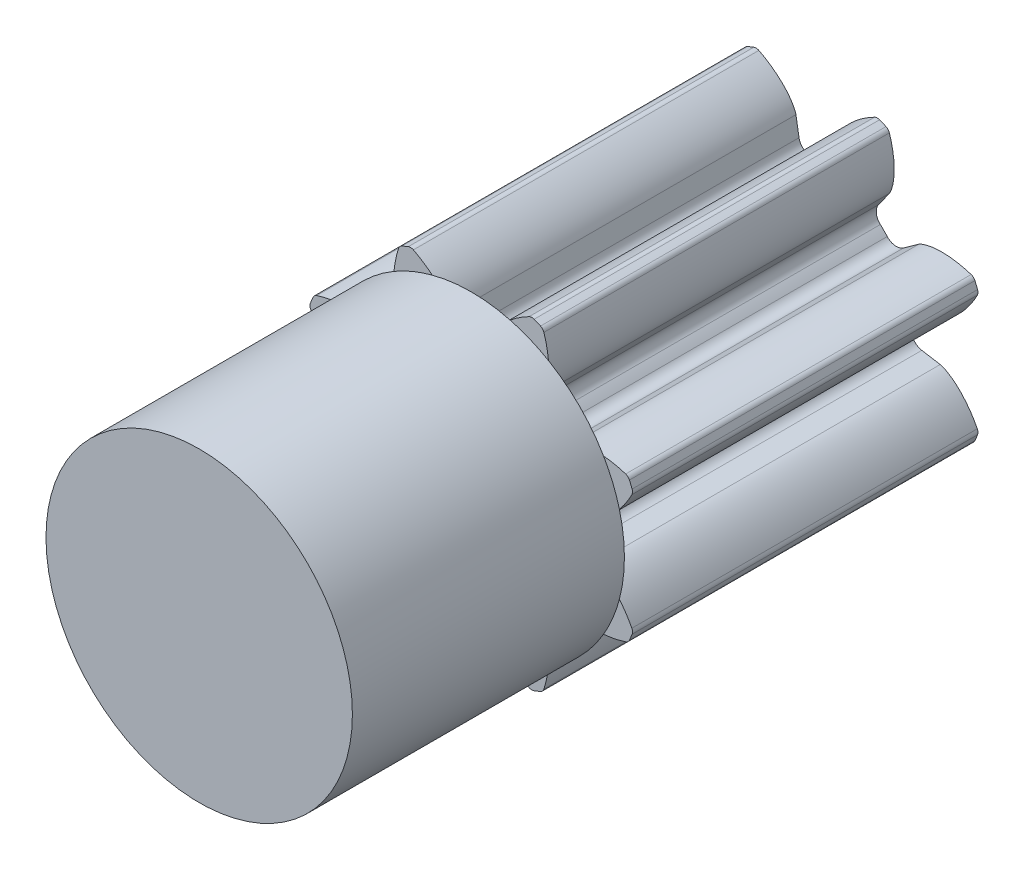
SolidWorks part; units mm, degrees
material "Alloy Steel"
ref_plane "Front" through (0, 0, 0) normal (0, 0, 1) x (1, 0, 0)
ref_plane "Top" through (0, 0, 0) normal (0, 1, 0) x (1, 0, 0)
ref_plane "Right" through (0, 0, 0) normal (1, 0, 0) x (0, 0, -1)
sketch "Sketch1" plane through (0, 0, 0) normal (0, 0, 1) x (1, 0, 0)
  circle A0 centre (0, 0) radius 6.35
extrude "Boss-Extrude1" add sketch "Sketch1" along normal blind 12.7
sketch "Sketch3" plane through (0, 0, 0) normal (0, 0, 1) x (1, 0, 0)
  line L0 (0, 0) -> (43.7181, 0) construction
  line L2 (0, 0) -> (-0.5784, 3.4443) construction
  line L3 (0, 0) -> (0.5784, 3.4443) construction
  line L4 (0.5784, 3.4443) -> (0.7625, 4.5405) construction
  line L5 (0, 0) -> (0, 61.276) construction
  line L6 (-0.5784, 3.4443) -> (-0.7625, 4.5405) construction
  circle A0 centre (0, 0) radius 6.35 construction
  circle A1 centre (0, 0) radius 5.08 construction
  circle A2 centre (0, 0) radius 4.604 construction
  arc A3 (0.5784, 3.4443) -> (-0.5784, 3.4443) centre (0, 0) ccw construction
  arc A5 (2.2164, 5.9506) -> (-2.2164, 5.9506) centre (0, 0) ccw
  spline S0 degree 4 poles (-0.7625, 4.5405) (-0.763, 4.5435) (-0.7648, 4.5519) (-0.7689, 4.5677) (-0.7767, 4.5932) (-0.7881, 4.6252) (-0.8045, 4.666) (-0.826, 4.7133) (-0.852, 4.7644) (-0.8825, 4.8189) (-0.9151, 4.8722) (-0.9496, 4.9244) (-0.9856, 4.9755) (-1.0311, 5.0363) (-1.0885, 5.1074) (-1.1594, 5.1881) (-1.2442, 5.2764) (-1.3353, 5.3629) (-1.4285, 5.4451) (-1.5269, 5.5244) (-1.6249, 5.5987) (-1.7306, 5.6719) (-1.8302, 5.7375) (-1.9458, 5.8065) (-2.0404, 5.8609) (-2.1692, 5.9277) (-2.2466, 5.9657) (-2.3384, 6.0084) (-2.3799, 6.0264) (-2.4054, 6.0376) knots 0 0 0 0 0 0.005377 0.015084 0.028532 0.04661 0.064855 0.092111 0.119476 0.146842 0.174209 0.201575 0.228941 0.256307 0.307035 0.361767 0.4165 0.471232 0.525964 0.580697 0.635429 0.690161 0.744894 0.799626 0.854358 0.909091 0.954545 1 1 1 1 1 construction
  spline S1 degree 4 poles (-0.7625, 4.5405) (-0.763, 4.5435) (-0.7648, 4.5519) (-0.7689, 4.5677) (-0.7767, 4.5932) (-0.7881, 4.6252) (-0.8045, 4.666) (-0.826, 4.7133) (-0.852, 4.7644) (-0.8825, 4.8189) (-0.9151, 4.8722) (-0.9496, 4.9244) (-0.9856, 4.9755) (-1.0311, 5.0363) (-1.0885, 5.1074) (-1.1594, 5.1881) (-1.2442, 5.2764) (-1.3353, 5.3629) (-1.4285, 5.4451) (-1.5269, 5.5244) (-1.6249, 5.5987) (-1.7306, 5.6719) (-1.8302, 5.7375) (-1.9458, 5.8065) (-2.0404, 5.8609) (-2.1413, 5.9133) (-2.1909, 5.9381) (-2.2164, 5.9506) knots 0 0 0 0 0 0.005377 0.015084 0.028532 0.04661 0.064855 0.092111 0.119476 0.146842 0.174209 0.201575 0.228941 0.256307 0.307035 0.361767 0.4165 0.471232 0.525964 0.580697 0.635429 0.690161 0.744894 0.799626 0.854358 0.909091 0.909091 0.909091 0.909091 0.909091
  spline S2 degree 4 poles (0.7625, 4.5405) (0.763, 4.5435) (0.7648, 4.5519) (0.7689, 4.5677) (0.7767, 4.5932) (0.7881, 4.6252) (0.8045, 4.666) (0.826, 4.7133) (0.852, 4.7644) (0.8825, 4.8189) (0.9151, 4.8722) (0.9496, 4.9244) (0.9856, 4.9755) (1.0311, 5.0363) (1.0885, 5.1074) (1.1594, 5.1881) (1.2442, 5.2764) (1.3353, 5.3629) (1.4285, 5.4451) (1.5269, 5.5244) (1.6249, 5.5987) (1.7306, 5.6719) (1.8302, 5.7375) (1.9458, 5.8065) (2.0404, 5.8609) (2.1692, 5.9277) (2.2466, 5.9657) (2.3384, 6.0084) (2.3799, 6.0264) (2.4054, 6.0376) knots 0 0 0 0 0 0.005377 0.015084 0.028532 0.04661 0.064855 0.092111 0.119476 0.146842 0.174209 0.201575 0.228941 0.256307 0.307035 0.361767 0.4165 0.471232 0.525964 0.580697 0.635429 0.690161 0.744894 0.799626 0.854358 0.909091 0.954545 1 1 1 1 1 construction
  spline S3 degree 4 poles (0.7625, 4.5405) (0.763, 4.5435) (0.7648, 4.5519) (0.7689, 4.5677) (0.7767, 4.5932) (0.7881, 4.6252) (0.8045, 4.666) (0.826, 4.7133) (0.852, 4.7644) (0.8825, 4.8189) (0.9151, 4.8722) (0.9496, 4.9244) (0.9856, 4.9755) (1.0311, 5.0363) (1.0885, 5.1074) (1.1594, 5.1881) (1.2442, 5.2764) (1.3353, 5.3629) (1.4285, 5.4451) (1.5269, 5.5244) (1.6249, 5.5987) (1.7306, 5.6719) (1.8302, 5.7375) (1.9458, 5.8065) (2.0404, 5.8609) (2.1413, 5.9133) (2.1909, 5.9381) (2.2164, 5.9506) knots 0 0 0 0 0 0.005377 0.015084 0.028532 0.04661 0.064855 0.092111 0.119476 0.146842 0.174209 0.201575 0.228941 0.256307 0.307035 0.361767 0.4165 0.471232 0.525964 0.580697 0.635429 0.690161 0.744894 0.799626 0.854358 0.909091 0.909091 0.909091 0.909091 0.909091
  point P0 (0, 3.4925)
sketch "DCLTBC" plane through (0, 0, 0) normal (0, 0, 1) x (1, 0, 0)
  line L0 (0, 0) -> (41.04, 0) construction
  line L1 (-0.5784, 3.4443) -> (-0.7625, 4.5405) construction
  line L2 (0.5784, 3.4443) -> (0.7625, 4.5405) construction
  line L3 (-0.5784, 3.4443) -> (-0.7625, 4.5405)
  line L4 (0.5784, 3.4443) -> (0.7625, 4.5405)
  line L5 (0, 0) -> (0, 104.9356) construction
  circle A0 centre (0, 0) radius 6.35
  circle A1 centre (0, 0) radius 5.08 construction
  circle A2 centre (0, 0) radius 4.604 construction
  arc A3 (0.5784, 3.4443) -> (-0.5784, 3.4443) centre (0, 0) ccw construction
  arc A4 (0.5784, 3.4443) -> (-0.5784, 3.4443) centre (0, 0) ccw
  spline S0 degree 4 poles (-985.3765, -170.0538) (-13.2322, 1.3996) (-0.8474, 3.8586) (-0.6755, 4.2604) (-0.7767, 4.5932) (-0.7881, 4.6252) (-0.8045, 4.666) (-0.826, 4.7133) (-0.852, 4.7644) (-0.8825, 4.8189) (-0.9151, 4.8722) (-0.9496, 4.9244) (-0.9856, 4.9755) (-1.0311, 5.0363) (-1.0885, 5.1074) (-1.1594, 5.1881) (-1.2442, 5.2764) (-1.3353, 5.3629) (-1.4285, 5.4451) (-1.5269, 5.5244) (-1.6249, 5.5987) (-1.7306, 5.6719) (-1.8302, 5.7375) (-1.9458, 5.8065) (-2.4469, 6.0948) (-4.2835, 6.892) (20.1681, -5.2427) (-900.8438, 444.5764) knots -0.5622 -0.5622 -0.5622 -0.5622 -0.5622 0.005377 0.015084 0.028532 0.04661 0.064855 0.092111 0.119476 0.146842 0.174209 0.201575 0.228941 0.256307 0.307035 0.361767 0.4165 0.471232 0.525964 0.580697 0.635429 0.690161 0.744894 0.799626 0.854358 1.850205 1.850205 1.850205 1.850205 1.850205 only from (-0.7625, 4.5405) to (-2.2164, 5.9506) construction
  spline S1 degree 4 poles (985.3765, -170.0538) (13.2322, 1.3996) (0.8474, 3.8586) (0.6755, 4.2604) (0.7767, 4.5932) (0.7881, 4.6252) (0.8045, 4.666) (0.826, 4.7133) (0.852, 4.7644) (0.8825, 4.8189) (0.9151, 4.8722) (0.9496, 4.9244) (0.9856, 4.9755) (1.0311, 5.0363) (1.0885, 5.1074) (1.1594, 5.1881) (1.2442, 5.2764) (1.3353, 5.3629) (1.4285, 5.4451) (1.5269, 5.5244) (1.6249, 5.5987) (1.7306, 5.6719) (1.8302, 5.7375) (1.9458, 5.8065) (2.4469, 6.0948) (4.2835, 6.892) (-20.1681, -5.2427) (900.8438, 444.5764) knots -0.5622 -0.5622 -0.5622 -0.5622 -0.5622 0.005377 0.015084 0.028532 0.04661 0.064855 0.092111 0.119476 0.146842 0.174209 0.201575 0.228941 0.256307 0.307035 0.361767 0.4165 0.471232 0.525964 0.580697 0.635429 0.690161 0.744894 0.799626 0.854358 1.850205 1.850205 1.850205 1.850205 1.850205 only from (0.7625, 4.5405) to (2.2164, 5.9506) construction
  spline S2 degree 4 poles (-0.7625, 4.5405) (-0.763, 4.5435) (-0.7648, 4.5519) (-0.7689, 4.5677) (-0.7767, 4.5932) (-0.7881, 4.6252) (-0.8045, 4.666) (-0.826, 4.7133) (-0.852, 4.7644) (-0.8825, 4.8189) (-0.9151, 4.8722) (-0.9496, 4.9244) (-0.9856, 4.9755) (-1.0311, 5.0363) (-1.0885, 5.1074) (-1.1594, 5.1881) (-1.2442, 5.2764) (-1.3353, 5.3629) (-1.4285, 5.4451) (-1.5269, 5.5244) (-1.6249, 5.5987) (-1.7306, 5.6719) (-1.8302, 5.7375) (-1.9458, 5.8065) (-2.0404, 5.8609) (-2.1413, 5.9133) (-2.1909, 5.9381) (-2.2164, 5.9506) knots 0 0 0 0 0 0.005377 0.015084 0.028532 0.04661 0.064855 0.092111 0.119476 0.146842 0.174209 0.201575 0.228941 0.256307 0.307035 0.361767 0.4165 0.471232 0.525964 0.580697 0.635429 0.690161 0.744894 0.799626 0.854358 0.909091 0.909091 0.909091 0.909091 0.909091
  spline S3 degree 4 poles (0.7625, 4.5405) (0.763, 4.5435) (0.7648, 4.5519) (0.7689, 4.5677) (0.7767, 4.5932) (0.7881, 4.6252) (0.8045, 4.666) (0.826, 4.7133) (0.852, 4.7644) (0.8825, 4.8189) (0.9151, 4.8722) (0.9496, 4.9244) (0.9856, 4.9755) (1.0311, 5.0363) (1.0885, 5.1074) (1.1594, 5.1881) (1.2442, 5.2764) (1.3353, 5.3629) (1.4285, 5.4451) (1.5269, 5.5244) (1.6249, 5.5987) (1.7306, 5.6719) (1.8302, 5.7375) (1.9458, 5.8065) (2.0404, 5.8609) (2.1413, 5.9133) (2.1909, 5.9381) (2.2164, 5.9506) knots 0 0 0 0 0 0.005377 0.015084 0.028532 0.04661 0.064855 0.092111 0.119476 0.146842 0.174209 0.201575 0.228941 0.256307 0.307035 0.361767 0.4165 0.471232 0.525964 0.580697 0.635429 0.690161 0.744894 0.799626 0.854358 0.909091 0.909091 0.909091 0.909091 0.909091
extrude "Cut-Extrude-DCLTBC" cut sketch "DCLTBC" along normal through all
fillet "Fillet-Tip-DCLTBC" radius 0.2258 2 edges at (2.2164, 5.9506, 6.35) (-2.2164, 5.9506, 6.35)
fillet "Fillet-Root-DCLTBC" radius 0.4517 2 edges at (-0.5784, 3.4443, 6.35) (0.5784, 3.4443, 6.35)
pattern_circular "CirPattern-DCLTBC" count 8 over 360 about axis through (0, 0, 12.7) along (0, 0, 1) of "Cut-Extrude-DCLTBC", "Fillet-Tip-DCLTBC", "Fillet-Root-DCLTBC"
sketch "Sketch4" plane through (0, 0, 12.7) normal (0, 0, 1) x (1, 0, 0)
  circle A0 centre (0, 0) radius 5.6319
  dimension "D1" = 11.2639
extrude "Boss-Extrude2" add sketch "Sketch4" along normal blind 10
equation "\"DiametralPitch\"= 20'Diametral Pitch"
equation "\"NumTeeth\"= 8'Number of Teeth"
equation "\"PressureAngle\"= 25deg'Pressure Angle"
equation "\"Addendum\"= 1 / \"DiametralPitch\"'Addendum"
equation "\"Dedendum\"= 1.25 / \"DiametralPitch\"'Dedendum"
equation "\"WorkingDepth\"= 2 / \"DiametralPitch\"'Working Depth - here for REF (Not used in building model)"
equation "\"WholeDepth\"= 2.25 / \"DiametralPitch\"'Whole Depth - here for REF (Not used in building model)"
equation "\"Clearance\"= .25 / \"DiametralPitch\"'Clearance"
equation "\"CircularPitch\"= pi / \"DiametralPitch\"'Circular Pitch - here for REF (Not used in building model)"
equation "\"PitchCircle\"= \"NumTeeth\" / \"DiametralPitch\"'Pitch Circle - or - Pitch Diameter"
equation "\"OutsideDiameter\"= ( \"NumTeeth\" + 2 ) / \"DiametralPitch\"'Outside Diameter"
equation "\"Fillet_Root\"= \"Clearance\" * cos ( \"PressureAngle\" ) * tan ( ( 90 + \"PressureAngle\" ) / 2 ) 'Fillet Root"
equation "\"AddendumCircle\"= \"PitchCircle\" + ( 2 * \"Addendum\" )'Addendum Circle - or - Addendum Diameter"
equation "\"DedendumCircle\"= \"PitchCircle\" - ( 2 * \"Dedendum\" )'Dedendum Circle - or - Dedendum Diameter"
equation "\"BaseCircle\"= \"PitchCircle\" * cos ( \"PressureAngle\" )'Base Circle - Base Diameter"
equation "\"PitchAngle\"= 360deg / \"NumTeeth\"'Pitch Angle"
equation "\"Alpha\"= sqr ( \"PitchCircle\" ^ 2 - \"BaseCircle\" ^ 2 ) / \"BaseCircle\" * 180 / PI - \"PressureAngle\"'Alpha - Used for Calculating Beta"
equation "\"Beta\"= ( \"PitchAngle\" / 4 - ( \"Alpha\" - 90 ) )'Beta - Used in definition of the parameters for the parametric equation driven curve"
equation "\"Gamma\"= ( \"PitchAngle\" / 4 - ( \"Alpha\" + 90 ) )'Gamma - Used in definition of the parameters for the parametric equation driven curve"
equation "\"Phi\"= sqr ( ( \"AddendumCircle\" / 2 ) ^ 2 - ( \"BaseCircle\" / 2 ) ^ 2 ) / ( \"BaseCircle\" / 2 )'Phi - Used in definition of the parameters for the parametric equation driven curve"
equation "\"DCGTBC\"= iif ( \"DedendumCircle\" > \"BaseCircle\" , \"unsuppressed\" , \"suppressed\" )'if Dedendum Circle IS GREATER THAN BaseCircle THEN UnsuppressORSuppress FEATURE"
equation "\"DCLTBC\"= iif ( \"DedendumCircle\" - .002 > \"BaseCircle\" , \"suppressed\" , \"unsuppressed\" )'if Dedendum Circle - .002 IS GREATER THAN BaseCircle THEN SuppressORUnsuppress FEATURE"
equation "\"Cut-Extrude-DCGTBC\"= iif ( \"DedendumCircle\" > \"BaseCircle\" , \"unsuppressed\" , \"suppressed\" )'if Dedendum Circle IS GREATER THAN BaseCircle THEN UnsuppressORSuppress FEATURE"
equation "\"Cut-Extrude-DCLTBC\"= iif ( \"DedendumCircle\" - .002 > \"BaseCircle\" , \"suppressed\" , \"unsuppressed\" )'if Dedendum Circle - .002 IS GREATER THAN BaseCircle THEN SuppressORUnsuppress FEATURE"
equation "\"CirPattern-DCGTBC\"= iif ( \"DedendumCircle\" > \"BaseCircle\" , \"unsuppressed\" , \"suppressed\" )'if Dedendum Circle IS GREATER THAN BaseCircle THEN UnsuppressORSuppress FEATURE"
equation "\"CirPattern-DCLTBC\"= iif ( \"DedendumCircle\" - .002 > \"BaseCircle\" , \"suppressed\" , \"unsuppressed\" )'if Dedendum Circle - .002 IS GREATER THAN BaseCircle THEN SuppressORUnsuppress FEATURE"
equation "\"Fillet-Tip-DCGTBC\"= iif ( \"DedendumCircle\" > \"BaseCircle\" , \"unsuppressed\" , \"suppressed\" )'if Dedendum Circle IS GREATER THAN BaseCircle THEN UnsuppressORSuppress FEATURE"
equation "\"Fillet-Tip-DCLTBC\"= iif ( \"DedendumCircle\" - .002 > \"BaseCircle\" , \"suppressed\" , \"unsuppressed\" )'if Dedendum Circle - .002 IS GREATER THAN BaseCircle THEN SuppressORUnsuppress FEATURE"
equation "\"Fillet-Root-DCLTBC\"= iif ( \"DedendumCircle\" - .002 > \"BaseCircle\" , \"suppressed\" , \"unsuppressed\" )'if Dedendum Circle - .002 IS GREATER THAN BaseCircle THEN SuppressORUnsuppress FEATURE"
equation "\"D1@CirPattern-DCGTBC\"= \"NumTeeth\"'Number of Teeth"
equation "\"D1@CirPattern-DCLTBC\"= \"NumTeeth\"'Number of Teeth"
equation "\"D1@Fillet-Tip-DCGTBC\"= \"Fillet_Root\" / 2 'Tip Rad For Large No of Teeth"
equation "\"D1@Fillet-Tip-DCLTBC\"=\"Fillet_Root\" / 2'Tip Rad For Small No of Teeth"
equation "\"D1@Fillet-Root-DCLTBC\"= \"Fillet_Root\"'Fillet Root"
